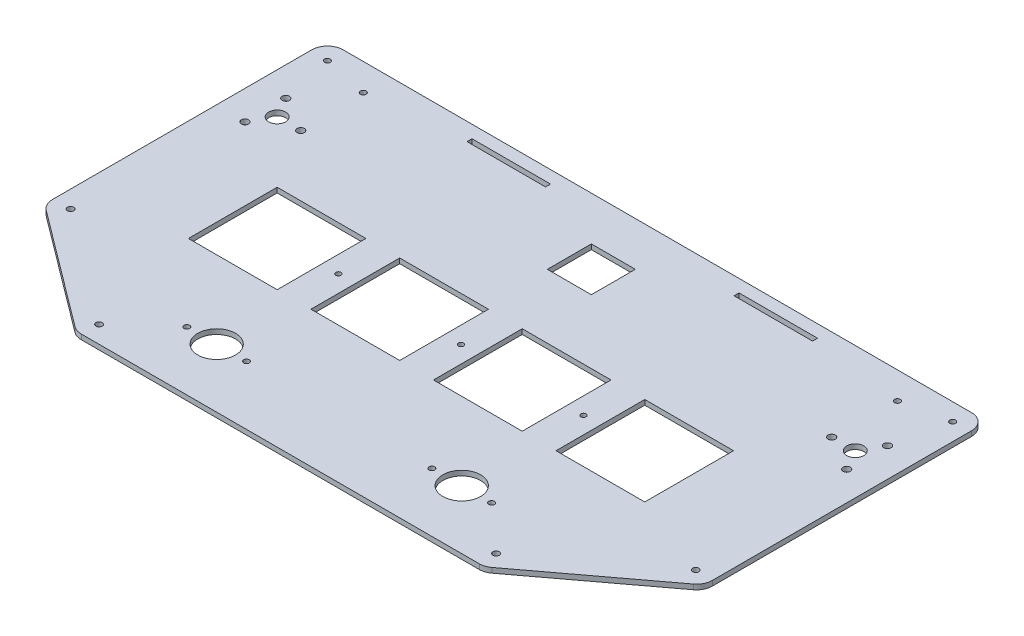
SolidWorks part; units mm, degrees
ref_plane "Front Plane" through (0, 0, 0) normal (0, 0, 1) x (1, 0, 0)
ref_plane "Top Plane" through (0, 0, 0) normal (0, 1, 0) x (1, 0, 0)
ref_plane "Right Plane" through (0, 0, 0) normal (1, 0, 0) x (0, 0, -1)
sketch "Sketch1" plane through (0, 0, 0) normal (0, 1, 0) x (1, 0, 0)
  line L0 (210, 240) -> (210, 0) construction
  line L1 (0, 0) -> (420, 0)
  line L2 (0, 0) -> (0, 240)
  line L3 (0, 240) -> (420, 240)
  line L4 (420, 0) -> (420, 240)
  line L5 (62, 115) -> (124, 115) construction
  line L6 (193, 215) -> (227, 215) construction
  line L7 (193, 215) -> (193, 181) construction
  line L8 (193, 181) -> (227, 181) construction
  line L9 (227, 215) -> (227, 181) construction
  line L10 (62, 84) -> (124, 84) construction
  line L11 (62, 84) -> (62, 146) construction
  line L12 (62, 146) -> (124, 146) construction
  line L13 (124, 84) -> (124, 146) construction
  line L14 (93, 146) -> (93, 84) construction
  line L15 (124, 84) -> (140, 84) construction
  line L16 (140, 84) -> (202, 84) construction
  line L17 (140, 84) -> (140, 146) construction
  line L18 (140, 146) -> (202, 146) construction
  line L19 (202, 84) -> (202, 146) construction
  line L20 (218, 84) -> (280, 84) construction
  line L21 (218, 84) -> (218, 146) construction
  line L22 (218, 146) -> (280, 146) construction
  line L23 (280, 84) -> (280, 146) construction
  line L24 (296, 84) -> (358, 84) construction
  line L25 (296, 84) -> (296, 146) construction
  line L26 (296, 146) -> (358, 146) construction
  line L27 (358, 84) -> (358, 146) construction
  line L28 (202, 84) -> (218, 84) construction
  line L29 (280, 84) -> (296, 84) construction
  line L30 (193, 198) -> (227, 198) construction
  line L31 (132, 84) -> (132, 54) construction
  line L32 (107, 21) -> (157, 21) construction
  line L33 (107, 21) -> (107, 54) construction
  line L34 (107, 54) -> (157, 54) construction
  line L35 (157, 21) -> (157, 54) construction
  line L36 (107, 37.5) -> (157, 37.5) construction
  line L37 (313, 21) -> (313, 54) construction
  line L38 (313, 54) -> (263, 54) construction
  line L39 (263, 21) -> (263, 54) construction
  line L40 (313, 21) -> (263, 21) construction
  line L41 (41, 182) -> (26, 182) construction
  line L42 (18.5, 194.9904) -> (18.5, 169.0096) construction
  line L43 (113, 37.5) -> (132, 37.5) construction
  line L44 (132, 37.5) -> (151, 37.5) construction
  line L45 (199.25, 143.25) -> (142.75, 143.25)
  line L46 (64.75, 143.25) -> (121.25, 143.25)
  line L47 (64.75, 143.25) -> (64.75, 86.75)
  line L48 (64.75, 86.75) -> (121.25, 86.75)
  line L49 (121.25, 143.25) -> (121.25, 86.75)
  line L50 (64.75, 143.25) -> (121.25, 86.75) construction
  line L51 (64.75, 86.75) -> (121.25, 143.25) construction
  line L52 (142.75, 143.25) -> (142.75, 86.75)
  line L53 (199.25, 86.75) -> (142.75, 86.75)
  line L54 (199.25, 143.25) -> (199.25, 86.75)
  line L55 (355.25, 86.75) -> (298.75, 86.75)
  line L56 (298.75, 143.25) -> (298.75, 86.75)
  line L57 (355.25, 143.25) -> (298.75, 143.25)
  line L58 (355.25, 143.25) -> (355.25, 86.75)
  line L59 (220.75, 143.25) -> (220.75, 86.75)
  line L60 (220.75, 86.75) -> (277.25, 86.75)
  line L61 (277.25, 143.25) -> (277.25, 86.75)
  line L62 (220.75, 143.25) -> (277.25, 143.25)
  line L64 (196, 212) -> (224, 212)
  line L65 (196, 212) -> (196, 184)
  line L66 (196, 184) -> (224, 184)
  line L67 (224, 212) -> (224, 184)
  line L68 (196, 212) -> (224, 184) construction
  line L69 (196, 184) -> (224, 212) construction
  circle A0 centre (26, 182) radius 15 construction
  circle A1 centre (41, 182) radius 2.3167
  circle A2 centre (18.5, 169.0096) radius 2.3167
  circle A3 centre (18.5, 194.9904) radius 2.3167
  circle A4 centre (26, 182) radius 5.4016
  circle A5 centre (132, 37.5) radius 12
  circle A6 centre (113, 37.5) radius 1.8
  circle A7 centre (151, 37.5) radius 1.8
  circle A8 centre (394, 182) radius 15 construction
  circle A9 centre (401.5, 194.9904) radius 2.3167
  circle A10 centre (379, 182) radius 2.3167
  circle A11 centre (394, 182) radius 5.4016
  circle A12 centre (401.5, 169.0096) radius 2.3167
  circle A13 centre (307, 37.5) radius 1.8
  circle A14 centre (269, 37.5) radius 1.8
  circle A15 centre (288, 37.5) radius 12
  point P11 (210, 215)
  point P20 (93, 115)
  point P58 (26, 182)
  point P63 (93, 115)
  point P80 (210, 198)
  dimension "D14" = 30
  dimension "D17" = 24
  dimension "D18" = 3.6
  dimension "D1" = 240
  dimension "D2" = 420
  dimension "D3" = 34
  dimension "D4" = 62
  dimension "D5" = 115
  dimension "D6" = 117
  dimension "D7" = 16
  dimension "D8" = 42
  dimension "D9" = 33
  dimension "D10" = 50
  dimension "D11" = 30
  dimension "D12" = 36
  dimension "D13" = 36
  dimension "D15" = 15
  dimension "D19" = 19
  dimension "D20" = 56.5
  dimension "D21" = 28
  dimension "D16" = 3
extrude "Boss-Extrude1" add sketch "Sketch1" along normal blind 3.175
sketch "Sketch2" plane through (0, 3.175, 0) normal (0, 1, 0) x (1, 0, 0)
  line L0 (0, 60) -> (0, 0)
  line L1 (0, 240) -> (0, 0) construction
  line L2 (0, 0) -> (80, 0)
  line L3 (0, 0) -> (420, 0) construction
  line L4 (80, 0) -> (0, 60)
  line L5 (420, 60) -> (420, 0)
  line L6 (420, 0) -> (420, 240) construction
  line L7 (420, 0) -> (340, 0)
  line L8 (340, 0) -> (420, 60)
  dimension "D1" = 80
  dimension "D2" = 60
extrude "Cut-Extrude1" cut sketch "Sketch2" against normal blind 10
fillet "Fillet1" radius 10 6 edges at (0, 1.5875, -60) (340, 1.5875, 0) (420, 1.5875, -240) (420, 1.5875, -60) (80, 1.5875, 0) (0, 1.5875, -240)
sketch "Sketch5" plane through (0, 3.175, 0) normal (0, 1, 0) x (1, 0, 0)
  line L0 (210, 240) -> (210, 0) construction
  line L1 (410, 240) -> (10, 240) construction
  line L2 (83.3333, 0) -> (336.6667, 0) construction
  line L3 (11, 65.5) -> (83.6667, 11) construction
  line L4 (77.3333, 2) -> (4, 57) construction
  line L5 (1.0557, 60.5279) -> (120, 120) construction
  line L6 (80.1711, 0.5132) -> (120, 120) construction
  line L7 (2.9289, 237.0711) -> (11, 229) construction
  line L8 (11, 229) -> (40, 229) construction
  line L9 (199.25, 115) -> (220.75, 115) construction
  line L10 (199.25, 86.75) -> (199.25, 143.25) construction
  line L11 (220.75, 143.25) -> (220.75, 86.75) construction
  line L12 (199.25, 115) -> (64.75, 115) construction
  line L13 (64.75, 143.25) -> (64.75, 86.75) construction
  line L14 (220.75, 115) -> (355.25, 115) construction
  line L15 (355.25, 86.75) -> (355.25, 143.25) construction
  line L16 (40, 229) -> (40, 222.825) construction
  circle A0 centre (11, 229) radius 1.83
  circle A2 centre (11, 65.5) radius 2
  circle A3 centre (83.6667, 11) radius 2
  arc A4 (0, 65) -> (4, 57) centre (10, 65) ccw construction
  arc A5 (77.3333, 2) -> (83.3333, 0) centre (83.3333, 10) ccw construction
  arc A6 (10, 240) -> (0, 230) centre (10, 230) ccw construction
  circle A9 centre (409, 65.5) radius 2
  circle A10 centre (336.3333, 11) radius 2
  circle A11 centre (210, 115) radius 1.66
  circle A12 centre (132, 115) radius 1.66
  circle A13 centre (288, 115) radius 1.66
  circle A14 centre (40, 222.825) radius 1.83
  circle A15 centre (380, 222.825) radius 1.83
  circle A16 centre (409, 229) radius 1.83
  point P26 (83.3333, 10)
  point P27 (10, 65)
  point P38 (10, 230)
  dimension "D2" = 4
  dimension "D5" = 3.32
  dimension "D7" = 3.66
  dimension "D1" = 11
  dimension "D3" = 11
  dimension "D4" = 29
  dimension "D6" = 6.175
extrude "Cut-Extrude2" cut sketch "Sketch5" against normal up to surface (3.175 mm away) up to face at (210, 0, -99.1853)
sketch "Sketch6" plane through (0, 3.175, 0) normal (0, 1, 0) x (1, 0, 0)
  line L0 (0, 230) -> (0, 65) construction
  line L1 (0, 228.825) -> (420, 228.825) construction
  line L2 (0, 228.825) -> (0, 232)
  line L3 (0, 232) -> (420, 232) construction
  line L4 (420, 228.825) -> (420, 232) construction
  line L5 (420, 65) -> (420, 230) construction
  line L6 (410, 240) -> (10, 240) construction
  line L7 (83.3333, 0) -> (336.6667, 0) construction
  line L8 (100, 232) -> (150, 232)
  line L9 (100, 232) -> (100, 228.825)
  line L10 (100, 228.825) -> (150, 228.825)
  line L11 (150, 232) -> (150, 228.825)
  line L12 (270, 232) -> (320, 232)
  line L13 (270, 232) -> (270, 228.825)
  line L14 (270, 228.825) -> (320, 228.825)
  line L15 (320, 232) -> (320, 228.825)
  line L16 (416, 57) -> (342.6667, 2) construction
  line L17 (73.3333, 5) -> (346.6667, 5) construction
  line L18 (73.3333, 5) -> (73.3333, 8.175)
  line L19 (73.3333, 8.175) -> (346.6667, 8.175) construction
  line L20 (346.6667, 5) -> (346.6667, 8.175) construction
  line L21 (77.3333, 2) -> (4, 57) construction
  line L23 (210, 5) -> (210, 0) construction
  line L24 (185, 8.175) -> (235, 8.175)
  line L25 (185, 8.175) -> (185, 5)
  line L26 (185, 5) -> (235, 5)
  line L27 (235, 8.175) -> (235, 5)
  dimension "D1" = 8
  dimension "D2" = 3.175
  dimension "D3" = 5
  dimension "D4" = 50
  dimension "D5" = 50
  dimension "D6" = 50
  dimension "D7" = 100
  dimension "D8" = 100
extrude "Cut-Extrude3" cut sketch "Sketch6" against normal up to surface (3.175 mm away) contours L8 L11 L10 L9 | L12 L15 L14 L13 up to face at (210, 0, -116.66)
